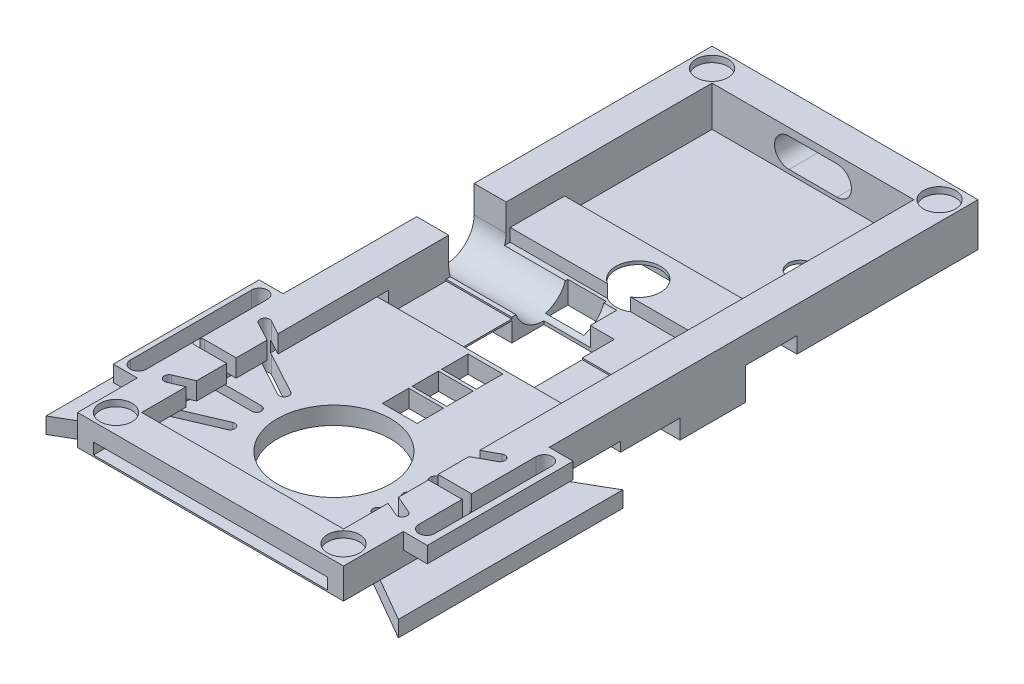
SolidWorks part; units mm, degrees
ref_plane "Front Plane" through (0, 0, 0) normal (0, 0, 1) x (1, 0, 0)
ref_plane "Top Plane" through (0, 0, 0) normal (0, 1, 0) x (1, 0, 0)
ref_plane "Right Plane" through (0, 0, 0) normal (1, 0, 0) x (0, 0, -1)
sketch "Sketch2" plane through (0, 0, 0) normal (0, 1, 0) x (1, 0, 0)
  line L1 (41.5, 99) -> (-41.5, 99)
  line L2 (41.5, 99) -> (41.5, -99)
  line L3 (41.5, -99) -> (-41.5, -99)
  line L4 (-41.5, 99) -> (-41.5, -99)
  line L5 (41.5, 99) -> (-41.5, -99) construction
  line L6 (41.5, -99) -> (-41.5, 99) construction
  point P0 (0, 0)
  dimension "D1" = 198
  dimension "D2" = 83
extrude "Boss-Extrude5" add sketch "Sketch2" along normal blind 2.5
sketch "Sketch5" plane through (0, 2.5, 0) normal (0, 1, 0) x (1, 0, 0)
  line L1 (41.5, 99) -> (-41.5, 99)
  line L2 (41.5, 99) -> (41.5, -99)
  line L3 (41.5, -99) -> (-41.5, -99)
  line L4 (-41.5, 99) -> (-41.5, -99)
  line L5 (41.5, 99) -> (-41.5, -99) construction
  line L6 (41.5, -99) -> (-41.5, 99) construction
  line L7 (31.5, 89) -> (-31.5, 89)
  line L8 (31.5, 89) -> (31.5, -89)
  line L9 (31.5, -89) -> (-31.5, -89)
  line L10 (-31.5, 89) -> (-31.5, -89)
  line L11 (31.5, 89) -> (-31.5, -89) construction
  line L12 (31.5, -89) -> (-31.5, 89) construction
  point P0 (0, 0)
  point P7 (0, 0)
  dimension "D1" = 178
  dimension "D2" = 63
extrude "Boss-Extrude6" add sketch "Sketch5" along normal blind 12
sketch "Sketch6" plane through (0, 14.5, 0) normal (0, 1, 0) x (1, 0, 0)
  line L0 (-41.5, -99) -> (41.5, -99) construction
  line L1 (-41.5, 99) -> (-41.5, -99) construction
  line L3 (41.5, 99) -> (-41.5, 99) construction
  line L4 (41.5, -99) -> (41.5, 99) construction
  circle A0 centre (-35.5, -93) radius 5
  circle A1 centre (35.5, -93) radius 5
  circle A2 centre (35.5, 93) radius 5
  circle A3 centre (-35.5, 93) radius 5
  dimension "D1" = 10
  dimension "D2" = 6
  dimension "D3" = 6
  dimension "D6" = 6
  dimension "D7" = 6
  dimension "D8" = 6
  dimension "D4" = 2
  dimension "D5" = 2
extrude "Cut-Extrude1" cut sketch "Sketch6" against normal blind 2
sketch "Sketch9" plane through (0, 0, 0) normal (0, -1, 0) x (-1, 0, 0)
  text T0 "COW-A-BUNGA" font "Cooper Black" height 3.5
extrude "Cut-Extrude2" cut sketch "Sketch9" against normal blind 1
sketch "Sketch11" plane through (0, 0, 0) normal (0, -1, 0) x (1, 0, 0)
  line L1 (-41.5, 99) -> (41.5, 99)
  line L2 (-41.5, 99) -> (-41.5, -99)
  line L3 (-41.5, -99) -> (41.5, -99)
  line L4 (41.5, 99) -> (41.5, -99)
extrude "Cut-Extrude4" cut sketch "Sketch11" against normal blind 3
sketch "Sketch12" plane through (0, 3, 0) normal (0, -1, 0) x (-1, 0, 0)
  line L0 (41.5, -99) -> (41.5, 99) construction
  line L1 (41.5, 43) -> (31.5, 43)
  line L2 (41.5, 43) -> (41.5, 89)
  line L4 (31.5, 43) -> (31.5, 89)
  line L5 (-41.5, 99) -> (-41.5, -99) construction
  line L6 (31.5, 89) -> (-31.5, 89)
  line L7 (41.5, 89) -> (41.5, 99)
  line L8 (41.5, 99) -> (-41.5, 99)
  line L9 (-41.5, 89) -> (-41.5, 99)
  line L11 (-31.5, 89) -> (-31.5, 43)
  line L12 (-31.5, 43) -> (-41.5, 43)
  line L13 (-41.5, 89) -> (-41.5, 43)
  point P17 (-36.5, 43)
  dimension "D1" = 56
  dimension "D2" = 56
extrude "Boss-Extrude9" add sketch "Sketch12" along normal blind 1
sketch "Sketch14" plane through (0, 2, 0) normal (0, -1, 0) x (1, 0, 0)
  line L1 (-41.5, -43) -> (41.5, -43)
  line L2 (-41.5, -43) -> (-41.5, -99)
  line L3 (-41.5, -99) -> (41.5, -99)
  line L4 (41.5, -43) -> (41.5, -99)
extrude "Boss-Extrude10" add sketch "Sketch14" along normal blind 1
sketch "Sketch15" plane through (0, 1, 0) normal (0, -1, 0) x (1, 0, 0)
  line L0 (-41.5, -99) -> (41.5, -99) construction
  line L1 (41.5, -99) -> (41.5, -43) construction
  circle A0 centre (20.25, -64.75) radius 3.75
  dimension "D1" = 7.5
  dimension "D2" = 34.25
  dimension "D3" = 21.25
sketch "Sketch16" plane through (0, 3, 0) normal (0, -1, 0) x (1, 0, 0)
  line L0 (41.5, -43) -> (41.5, 99) construction
  line L1 (-41.5, -43) -> (41.5, -43)
  line L2 (-41.5, -43) -> (-41.5, -26)
  line L3 (-41.5, -26) -> (41.5, -26)
  line L4 (41.5, -43) -> (41.5, -26)
  line L6 (-41.5, -26) -> (41.5, -26)
  line L7 (-41.5, -26) -> (-41.5, -6)
  line L8 (-41.5, -6) -> (41.5, -6)
  line L9 (41.5, -26) -> (41.5, -6)
  dimension "D1" = 17
  dimension "D2" = 20
extrude "Cut-Extrude6" cut sketch "Sketch16" against normal blind 4 contours L3 L4 L1 L2
sketch "Sketch17" plane through (0, 7, 0) normal (0, -1, 0) x (1, 0, 0)
  line L1 (-41.5, -26) -> (41.5, -26)
  line L2 (-41.5, -26) -> (-41.5, -43)
  line L3 (-41.5, -43) -> (41.5, -43)
  line L4 (41.5, -26) -> (41.5, -43)
extrude "Boss-Extrude13" add sketch "Sketch17" along normal blind 1
sketch "Sketch19" plane through (0, 0, -43) normal (0, 0, 1) x (1, 0, 0)
  line L1 (-41.5, 6) -> (41.5, 6)
  line L2 (-41.5, 6) -> (-41.5, 1)
  line L3 (-41.5, 1) -> (41.5, 1)
  line L4 (41.5, 6) -> (41.5, 1)
extrude "Boss-Extrude18" add sketch "Sketch19" along normal blind 0.5
sketch "Sketch20" plane through (0, 3, 0) normal (0, -1, 0) x (1, 0, 0)
  line L0 (41.5, -26) -> (41.5, 99) construction
  line L1 (-41.5, -26) -> (41.5, -26)
  line L2 (-41.5, -26) -> (-41.5, -6)
  line L3 (-41.5, -6) -> (41.5, -6)
  line L4 (41.5, -26) -> (41.5, -6)
  dimension "D1" = 20
extrude "Boss-Extrude22" add sketch "Sketch20" along normal blind 7
sketch "Sketch22" plane through (0, 0, -26) normal (0, 0, -1) x (-1, 0, 0)
  line L1 (-41.5, 6) -> (41.5, 6)
  line L2 (-41.5, 6) -> (-41.5, -4)
  line L3 (-41.5, -4) -> (41.5, -4)
  line L4 (41.5, 6) -> (41.5, -4)
extrude "Boss-Extrude23" add sketch "Sketch22" along normal blind 0.5
sketch "Sketch23" plane through (0, 3, 0) normal (0, -1, 0) x (-1, 0, 0)
  line L1 (-41.5, 6) -> (41.5, 6)
  line L2 (-41.5, 6) -> (-41.5, -99)
  line L3 (-41.5, -99) -> (41.5, -99)
  line L4 (41.5, 6) -> (41.5, -99)
extrude "Cut-Extrude8" cut sketch "Sketch23" against normal blind 3
sketch "Sketch26" plane through (0, 6, 0) normal (0, -1, 0) x (-1, 0, 0)
  line L0 (31.5, -89) -> (31.5, 6) construction
  line L1 (41.5, 6) -> (31.5, 6)
  line L2 (41.5, 6) -> (41.5, -12)
  line L3 (41.5, -12) -> (31.5, -12)
  line L4 (31.5, 6) -> (31.5, -12)
  line L5 (-41.5, 6) -> (-41.5, -99) construction
  line L6 (-31.5, 6) -> (-41.5, 6)
  line L7 (-31.5, 6) -> (-31.5, -12)
  line L8 (-31.5, -12) -> (-41.5, -12)
  line L9 (-41.5, 6) -> (-41.5, -12)
  dimension "D1" = 18
  dimension "D2" = 18
extrude "Boss-Extrude28" add sketch "Sketch26" along normal blind 3.5
sketch "Sketch27" plane through (0, 2.5, 0) normal (0, -1, 0) x (1, 0, 0)
  line L1 (-41.5, 12) -> (41.5, 12)
  line L2 (-41.5, 12) -> (-41.5, -6)
  line L3 (-41.5, -6) -> (41.5, -6)
  line L4 (41.5, 12) -> (41.5, -6)
extrude "Boss-Extrude29" add sketch "Sketch27" along normal blind 0.5
sketch "Sketch28" plane through (0, 6, 0) normal (0, -1, 0) x (1, 0, 0)
  line L1 (-41.5, 12) -> (41.5, 12)
  line L2 (-41.5, 12) -> (-41.5, 99)
  line L3 (-41.5, 99) -> (41.5, 99)
  line L4 (41.5, 12) -> (41.5, 99)
extrude "Cut-Extrude9" cut sketch "Sketch28" against normal blind 3
sketch "Sketch29" plane through (0, 9, 0) normal (0, -1, 0) x (-1, 0, 0)
  line L0 (-41.5, -99) -> (41.5, -99) construction
  line L1 (41.5, -12) -> (36.5, -12)
  line L2 (41.5, -12) -> (41.5, -99)
  line L3 (41.5, -99) -> (36.5, -99)
  line L4 (36.5, -12) -> (36.5, -99)
  dimension "D1" = 5
extrude "Boss-Extrude34" add sketch "Sketch29" along normal blind 3.5
sketch "Sketch30" plane through (0, 9, 0) normal (0, -1, 0) x (-1, 0, 0)
  line L0 (-41.5, -99) -> (36.5, -99) construction
  line L1 (-41.5, -12) -> (-36.5, -12)
  line L2 (-41.5, -12) -> (-41.5, -99)
  line L3 (-41.5, -99) -> (-36.5, -99)
  line L4 (-36.5, -12) -> (-36.5, -99)
  dimension "D1" = 5
extrude "Boss-Extrude35" add sketch "Sketch30" along normal blind 3.5
sketch "Sketch31" plane through (0, 5.5, 0) normal (0, -1, 0) x (-1, 0, 0)
  line L1 (41.5, -12) -> (-41.5, -12)
  line L2 (41.5, -12) -> (41.5, -99)
  line L3 (41.5, -99) -> (-41.5, -99)
  line L4 (-41.5, -12) -> (-41.5, -99)
extrude "Boss-Extrude36" add sketch "Sketch31" along normal blind 0.5
sketch "Sketch32" plane through (0, 0, 12) normal (0, 0, 1) x (1, 0, 0)
  line L1 (-41.5, 5) -> (41.5, 5)
  line L2 (-41.5, 5) -> (-41.5, 2)
  line L3 (-41.5, 2) -> (41.5, 2)
  line L4 (41.5, 5) -> (41.5, 2)
extrude "Boss-Extrude37" add sketch "Sketch32" along normal blind 0.5
sketch "Sketch33" plane through (0, 5, 0) normal (0, -1, 0) x (1, 0, 0)
  line L0 (-41.5, 99) -> (-41.5, 12.5) construction
  line L1 (41.5, 99) -> (-41.5, 99) construction
  line L2 (41.5, 12.5) -> (-41.5, 12.5) construction
  line L3 (-6, 40.5) -> (6, 40.5)
  line L4 (-6, 40.5) -> (-6, 12.5)
  line L5 (-6, 12.5) -> (6, 12.5)
  line L6 (6, 40.5) -> (6, 12.5)
  line L7 (41.5, 12.5) -> (41.5, 99) construction
  circle A0 centre (0, 60.5) radius 18.5
  dimension "D1" = 37
  dimension "D2" = 41.5
  dimension "D3" = 38.5
  dimension "D4" = 47.5
  dimension "D5" = 47.5
  dimension "D6" = 28
extrude "Boss-Extrude39" add sketch "Sketch33" along normal blind 5
sketch "Sketch35" plane through (0, 0, 0) normal (0, -1, 0) x (1, 0, 0)
  line L0 (-18.5, 60.5) -> (18.5, 60.5) construction
  line L1 (0, 79) -> (0, 42)
  circle A0 centre (0, 60.5) radius 18.5 construction
  circle A1 centre (0, 60.5) radius 17.6713
extrude "Cut-Extrude11" cut sketch "Sketch35" against normal blind 25 contours A1
sketch "Sketch36" plane through (0, 0, 0) normal (0, -1, 0) x (-1, 0, 0)
  line L0 (6, -12.5) -> (-6, -12.5) construction
  line L1 (5.3705, -40) -> (-5.4626, -40)
  line L2 (5.3705, -40) -> (5.3705, -31.75)
  line L3 (5.3705, -31.75) -> (-5.4626, -31.75)
  line L4 (-5.4626, -40) -> (-5.4626, -31.75)
  line L5 (5.3705, -30.75) -> (-5.4626, -30.75)
  line L6 (5.3705, -30.75) -> (5.3705, -22.5)
  line L7 (5.3705, -22.5) -> (-5.4626, -22.5)
  line L8 (-5.4626, -30.75) -> (-5.4626, -22.5)
  line L9 (5.3705, -21.5) -> (-5.4626, -21.5)
  line L10 (5.3705, -21.5) -> (5.3705, -13.25)
  line L11 (5.3705, -13.25) -> (-5.4626, -13.25)
  line L12 (-5.4626, -21.5) -> (-5.4626, -13.25)
  dimension "D1" = 8.25
  dimension "D2" = 8.25
  dimension "D3" = 8.25
  dimension "D4" = 0.75
  dimension "D5" = 1
  dimension "D6" = 1
extrude "Cut-Extrude12" cut sketch "Sketch36" against normal blind 25
sketch "Sketch37" plane through (0, 5, 0) normal (0, -1, 0) x (-1, 0, 0)
  line L0 (-16.0152, -72.861) -> (-54.9864, -95.361)
  line L1 (-54.9864, -95.361) -> (-54.9864, -25.3367)
  line L2 (-54.9864, -25.3367) -> (-16.0152, -47.8367)
  line L3 (0, -42.8287) -> (0, -79) construction
  line L4 (54.9864, -95.361) -> (54.9864, -25.3367)
  line L5 (16.0152, -72.861) -> (54.9864, -95.361)
  line L6 (54.9864, -25.3367) -> (16.0152, -47.8367)
  arc A0 (-16.0152, -47.8367) -> (-16.0152, -72.861) centre (-3.5031, -60.3488) ccw
  circle A1 centre (0, -60.5) radius 17.6713 construction
  circle A2 centre (0, -60.5) radius 18.5 construction
  arc A3 (16.0152, -47.8367) -> (16.0152, -72.861) centre (3.5031, -60.3488) cw
  dimension "D1" = 60
  dimension "D2" = 60
  dimension "D3" = 45
extrude "Boss-Extrude42" add sketch "Sketch37" along normal blind 5
sketch "Sketch38" plane through (0, -4, 0) normal (0, -1, 0) x (1, 0, 0)
  line L0 (41.5, 99) -> (-41.5, 99) construction
  line L1 (-11, -16) -> (11, -16)
  line L2 (-11, -16) -> (-11, 12)
  line L3 (-11, 12) -> (11, 12)
  line L4 (11, -16) -> (11, 12)
  line L5 (41.5, -6) -> (41.5, 12.5) construction
  point P6 (0, -16)
  dimension "D1" = 115
  dimension "D2" = 28
  dimension "D3" = 22
  dimension "D4" = 52.5
extrude "Cut-Extrude13" cut sketch "Sketch38" against normal blind 25
sketch "Sketch39" plane through (0, -4, 0) normal (0, -1, 0) x (1, 0, 0)
  line L1 (-12.5, -18) -> (-0.5, -18)
  line L2 (-12.5, -18) -> (-12.5, -25)
  line L3 (-12.5, -25) -> (-0.5, -25)
  line L4 (-0.5, -18) -> (-0.5, -25)
  line L6 (-41.5, -99) -> (41.5, -99) construction
  line L7 (41.5, -26.5) -> (41.5, -6) construction
  circle A0 centre (2.4851, -32) radius 7
  point P6 (-12.5, -21.5)
  dimension "D5" = 14
  dimension "D6" = 67
  dimension "D1" = 81
  dimension "D2" = 7
  dimension "D3" = 54
  dimension "D4" = 12
extrude "Cut-Extrude14" cut sketch "Sketch39" against normal blind 25
extrude "Cut-Extrude15" cut sketch "Sketch15" against normal blind 25 contours A0
sketch "Sketch40" plane through (-41.5, 0, 0) normal (-1, 0, 0) x (0, 0, 1)
  line L0 (-15.7893, 47.6037) -> (-15.7893, 5.9968) construction
  line L1 (-6.8278, 47.6037) -> (-6.8278, 5.9968)
  line L2 (-24.7508, 47.6037) -> (-24.7508, 5.9968)
  arc A0 (-6.8278, 47.6037) -> (-24.7508, 47.6037) centre (-15.7893, 47.6037) ccw
  arc A1 (-24.7508, 5.9968) -> (-6.8278, 5.9968) centre (-15.7893, 5.9968) ccw
  point P2 (-15.7893, 26.8003)
extrude "Cut-Extrude17" cut sketch "Sketch40" against normal blind 45
sketch "Sketch41" plane through (41.5, 0, 0) normal (1, 0, 0) x (0, 0, -1)
  line L0 (-99, 14.5) -> (99, 14.5) construction
  line L1 (-80.3542, 14.5) -> (-34.8306, 14.5)
  line L2 (-80.3542, 14.5) -> (-80.3542, 9.5)
  line L3 (-80.3542, 9.5) -> (-34.8306, 9.5)
  line L4 (-34.8306, 14.5) -> (-34.8306, 9.5)
  dimension "D1" = 5
extrude "Boss-Extrude44" add sketch "Sketch41" along normal blind 7.5
sketch "Sketch42" plane through (0, 14.5, 0) normal (0, 1, 0) x (1, 0, 0)
  line L0 (44.4812, -39.3477) -> (44.4812, -75.9668) construction
  line L1 (46.9812, -39.3477) -> (46.9812, -75.9668)
  line L2 (41.9812, -39.3477) -> (41.9812, -75.9668)
  arc A0 (46.9812, -39.3477) -> (41.9812, -39.3477) centre (44.4812, -39.3477) ccw
  arc A1 (41.9812, -75.9668) -> (46.9812, -75.9668) centre (44.4812, -75.9668) ccw
  point P2 (44.4812, -57.6573)
  dimension "D1" = 5
extrude "Cut-Extrude18" cut sketch "Sketch42" against normal blind 7.5
sketch "Sketch43" plane through (0, 14.5, 0) normal (0, 1, 0) x (1, 0, 0)
  line L0 (41.5, -34.8306) -> (-41.5, -34.8306) construction
  line L1 (-41.5, 6.8278) -> (-41.5, -99) construction
  line L2 (41.5, -80.3542) -> (-41.5, -80.3542) construction
  line L4 (-41.5, -34.8306) -> (-49, -34.8306)
  line L5 (-41.5, -34.8306) -> (-41.5, -80.3542)
  line L6 (-41.5, -80.3542) -> (-49, -80.3542)
  line L7 (-49, -34.8306) -> (-49, -80.3542)
  dimension "D1" = 7.5
extrude "Boss-Extrude46" add sketch "Sketch43" against normal blind 5
sketch "Sketch44" plane through (0, 14.5, 0) normal (0, 1, 0) x (1, 0, 0)
  line L0 (-44.9421, -38.7585) -> (-44.9421, -76.5876) construction
  line L1 (-42.4421, -38.7585) -> (-42.4421, -76.5876)
  line L2 (-47.4421, -38.7585) -> (-47.4421, -76.5876)
  arc A0 (-42.4421, -38.7585) -> (-47.4421, -38.7585) centre (-44.9421, -38.7585) ccw
  arc A1 (-47.4421, -76.5876) -> (-42.4421, -76.5876) centre (-44.9421, -76.5876) ccw
  point P2 (-44.9421, -57.6731)
  dimension "D1" = 5
extrude "Cut-Extrude19" cut sketch "Sketch44" against normal blind 5
sketch "Sketch46" plane through (0, 0, -99) normal (0, 0, -1) x (-1, 0, 0)
  line L0 (7.5, 7.6848) -> (-7.5, 7.6848) construction
  line L1 (7.5, 3.1848) -> (-7.5, 3.1848)
  line L2 (7.5, 12.1848) -> (-7.5, 12.1848)
  line L3 (-41.5, 9.5) -> (-41.5, 14.5) construction
  arc A0 (7.5, 3.1848) -> (7.5, 12.1848) centre (7.5, 7.6848) ccw
  arc A1 (-7.5, 12.1848) -> (-7.5, 3.1848) centre (-7.5, 7.6848) ccw
  point P2 (0, 7.6848)
  dimension "D1" = 15
  dimension "D2" = 41.5
  dimension "D3" = 9
extrude "Cut-Extrude20" cut sketch "Sketch46" against normal blind 15
sketch "Sketch47" plane through (0, 0, 0) normal (0, -1, 0) x (-1, 0, 0)
  line L0 (-23.6471, -60.9929) -> (-41.434, -60.9929) construction
  line L1 (-23.6471, -62.4929) -> (-41.434, -62.4929)
  line L2 (-23.6471, -59.4929) -> (-41.434, -59.4929)
  line L3 (-23.5161, -52.4991) -> (-36.7134, -45.3342) construction
  line L4 (-24.2318, -53.8173) -> (-37.429, -46.6524)
  line L5 (-22.8004, -51.1808) -> (-35.9977, -44.0159)
  line L6 (-23.0572, -69.8686) -> (-36.3509, -75.5543) construction
  line L7 (-22.4674, -71.2477) -> (-35.761, -76.9335)
  line L8 (-23.6471, -68.4894) -> (-36.9407, -74.1752)
  line L9 (0, -42.8287) -> (0, -78.1713) construction
  line L10 (23.0572, -69.8686) -> (36.3509, -75.5543) construction
  line L11 (22.4674, -71.2477) -> (35.761, -76.9335)
  line L12 (23.6471, -68.4894) -> (36.9407, -74.1752)
  line L13 (23.6471, -60.9929) -> (41.434, -60.9929) construction
  line L14 (23.6471, -62.4929) -> (41.434, -62.4929)
  line L15 (23.6471, -59.4929) -> (41.434, -59.4929)
  line L16 (23.5161, -52.4991) -> (36.7134, -45.3342) construction
  line L17 (24.2318, -53.8173) -> (37.429, -46.6524)
  line L18 (22.8004, -51.1808) -> (35.9977, -44.0159)
  arc A0 (-23.6471, -62.4929) -> (-23.6471, -59.4929) centre (-23.6471, -60.9929) ccw
  arc A1 (-41.434, -59.4929) -> (-41.434, -62.4929) centre (-41.434, -60.9929) ccw
  arc A2 (-24.2318, -53.8173) -> (-22.8004, -51.1808) centre (-23.5161, -52.4991) ccw
  arc A3 (-35.9977, -44.0159) -> (-37.429, -46.6524) centre (-36.7134, -45.3342) ccw
  arc A4 (-22.4674, -71.2477) -> (-23.6471, -68.4894) centre (-23.0572, -69.8686) ccw
  arc A5 (-36.9407, -74.1752) -> (-35.761, -76.9335) centre (-36.3509, -75.5543) ccw
  circle A6 centre (0, -60.5) radius 17.6713 construction
  arc A7 (22.4674, -71.2477) -> (23.6471, -68.4894) centre (23.0572, -69.8686) cw
  arc A8 (36.9407, -74.1752) -> (35.761, -76.9335) centre (36.3509, -75.5543) cw
  arc A9 (23.6471, -62.4929) -> (23.6471, -59.4929) centre (23.6471, -60.9929) cw
  arc A10 (41.434, -59.4929) -> (41.434, -62.4929) centre (41.434, -60.9929) cw
  arc A11 (24.2318, -53.8173) -> (22.8004, -51.1808) centre (23.5161, -52.4991) cw
  arc A12 (35.9977, -44.0159) -> (37.429, -46.6524) centre (36.7134, -45.3342) cw
  point P2 (-32.5405, -60.9929)
  point P7 (-30.1147, -48.9166)
  point P14 (-29.704, -72.7114)
  point P23 (29.704, -72.7114)
  point P35 (32.5405, -60.9929)
  point P42 (30.1147, -48.9166)
  dimension "D1" = 3
  dimension "D2" = 3
  dimension "D3" = 3
extrude "Cut-Extrude23" cut sketch "Sketch47" against normal blind 15
